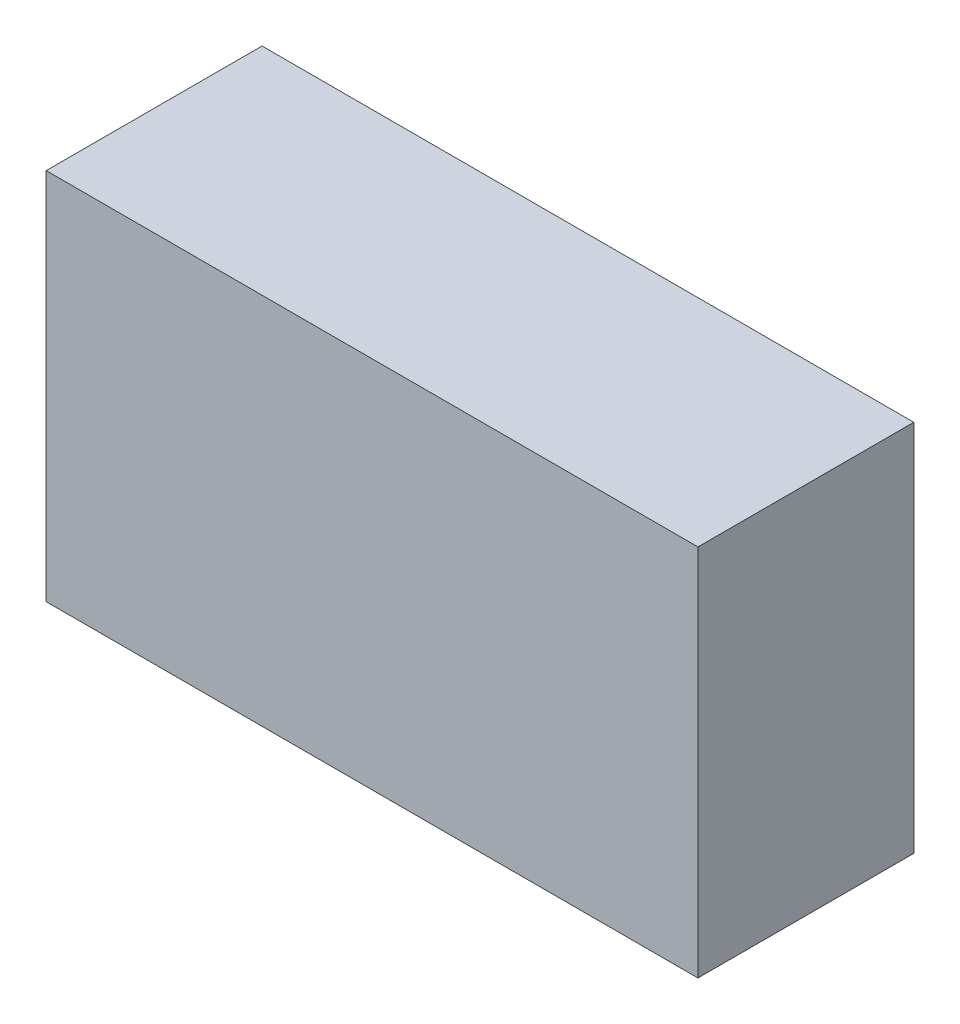
SolidWorks part; units mm, degrees
ref_plane "Front Plane" through (0, 0, 0) normal (0, 0, 1) x (1, 0, 0)
ref_plane "Top Plane" through (0, 0, 0) normal (0, 1, 0) x (1, 0, 0)
ref_plane "Right Plane" through (0, 0, 0) normal (1, 0, 0) x (0, 0, -1)
sketch "Sketch1" plane through (0, 0, 0) normal (0, 0, 1) x (1, 0, 0)
  line L0 (56.9445, 30.39) -> (79.2368, 30.39) construction
  line L1 (57.1445, 30.19) -> (79.0368, 30.19)
  line L2 (57.1445, 30.19) -> (57.1445, 17.65)
  line L3 (57.1445, 17.65) -> (79.0368, 17.65)
  line L4 (79.0368, 30.19) -> (79.0368, 17.65)
  line L5 (79.2368, 17.45) -> (79.2368, 30.39) construction
  line L6 (79.2368, 17.45) -> (56.9445, 17.45) construction
  line L7 (56.9445, 17.45) -> (56.9445, 30.39) construction
  dimension "D1" = 0.2
  dimension "D2" = 0.2
  dimension "D3" = 0.2
  dimension "D4" = 0.2
extrude "Boss-Extrude1" add sketch "Sketch1" along normal blind 7.25
shell "Shell1" thickness 0.5
equation "\"D2@Sketch1\"=\"D1@Sketch1\""
equation "\"D3@Sketch1\"=\"D1@Sketch1\""
equation "\"D4@Sketch1\"=\"D1@Sketch1\""
